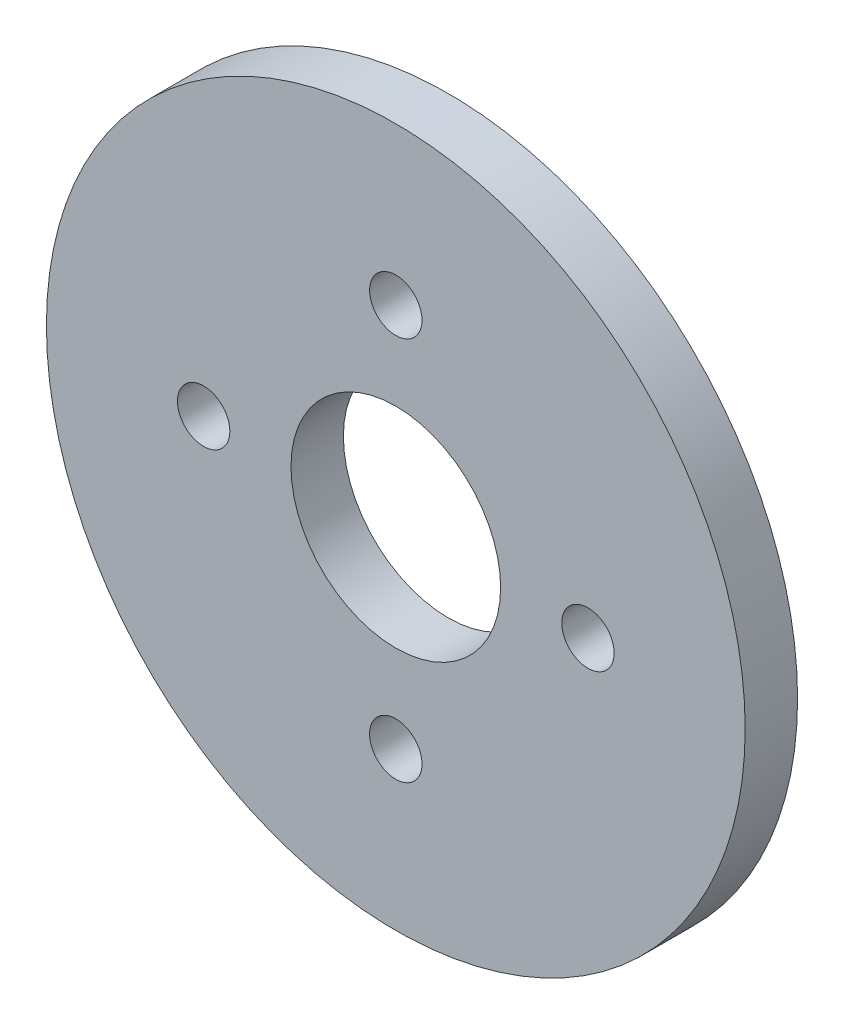
SolidWorks part; units mm, degrees
ref_plane "Front" through (0, 0, 0) normal (0, 0, 1) x (1, 0, 0)
ref_plane "Top" through (0, 0, 0) normal (0, 1, 0) x (1, 0, 0)
ref_plane "Right" through (0, 0, 0) normal (1, 0, 0) x (0, 0, -1)
sketch "草图1" plane through (0, 0, 0) normal (0, 0, 1) x (1, 0, 0)
  circle A0 centre (0, 0) radius 20
  circle A1 centre (0, 0) radius 11 construction
  circle A2 centre (0, 11) radius 1.5
  circle A3 centre (11, 0) radius 1.5
  circle A4 centre (0, -11) radius 1.5
  circle A5 centre (-11, 0) radius 1.5
  point P15 (0, 0)
  dimension "D1" = 40
  dimension "D2" = 4
extrude "凸台-拉伸1" add sketch "草图1" along normal blind 3
sketch "草图2" plane through (0, 0, 3) normal (0, 0, 1) x (1, 0, 0)
  circle A1 centre (0, 0) radius 6
extrude "切除-拉伸1" cut sketch "草图2" against normal through all
